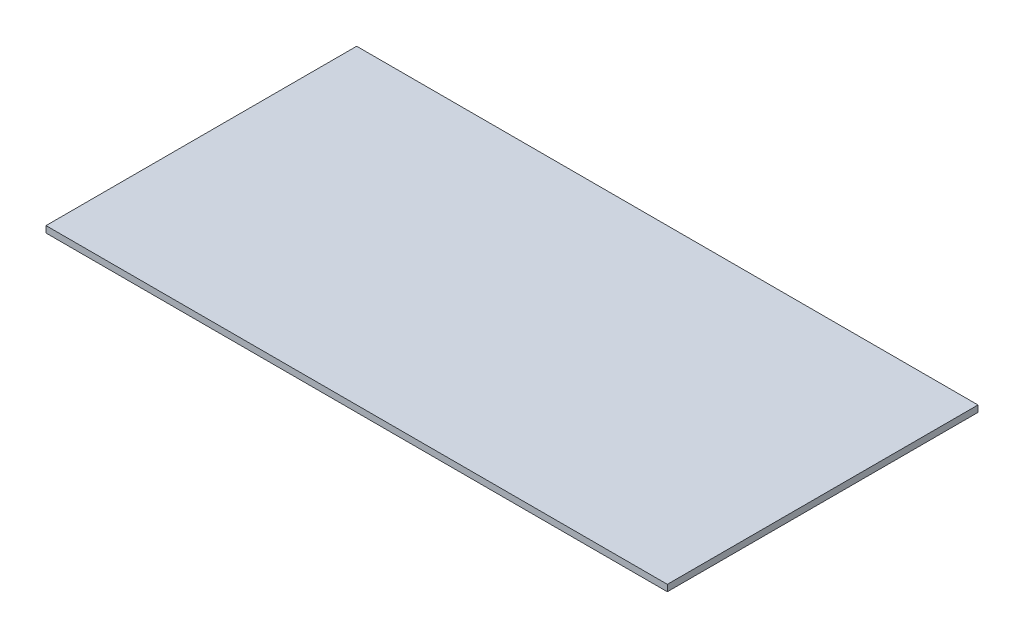
SolidWorks part; units mm, degrees
ref_plane "Front Plane" through (0, 0, 0) normal (0, 0, 1) x (1, 0, 0)
ref_plane "Top Plane" through (0, 0, 0) normal (0, 1, 0) x (1, 0, 0)
ref_plane "Right Plane" through (0, 0, 0) normal (1, 0, 0) x (0, 0, -1)
sketch "Sketch1" plane through (0, 0, 0) normal (0, 1, 0) x (1, 0, 0)
  line L1 (-609.6, 304.8) -> (609.6, 304.8)
  line L2 (-609.6, 304.8) -> (-609.6, -304.8)
  line L3 (-609.6, -304.8) -> (609.6, -304.8)
  line L4 (609.6, 304.8) -> (609.6, -304.8)
  dimension "D1" = 1219.2
  dimension "D2" = 609.6
  dimension "D3" = 609.6
  dimension "D4" = 304.8
extrude "Boss-Extrude1" add sketch "Sketch1" along normal blind 12.7
